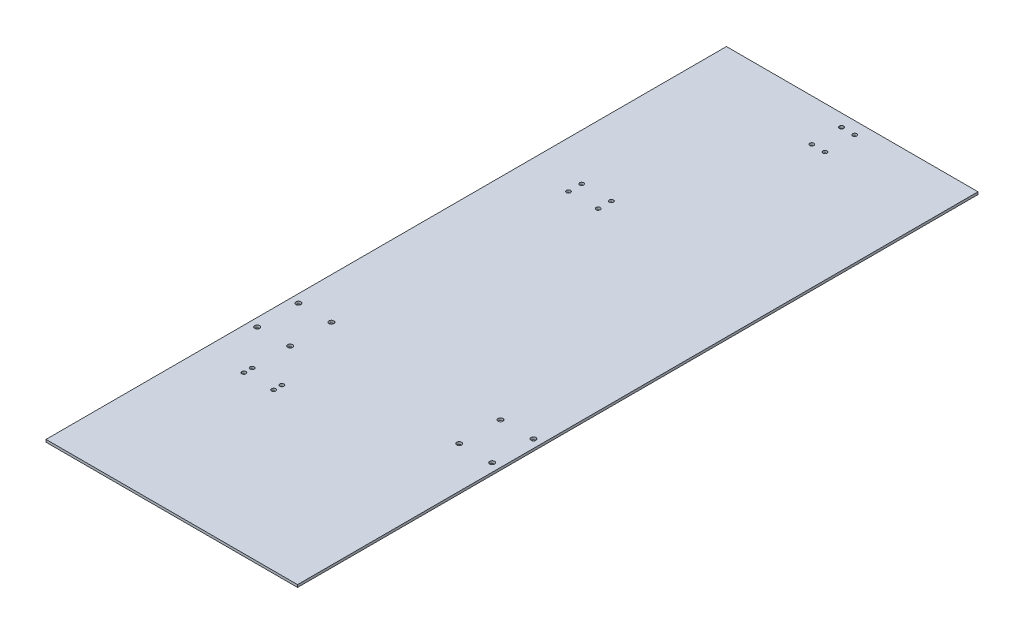
SolidWorks part; units mm, degrees
ref_plane "Front Plane" through (0, 0, 0) normal (0, 0, 1) x (1, 0, 0)
ref_plane "Top Plane" through (0, 0, 0) normal (0, 1, 0) x (1, 0, 0)
ref_plane "Right Plane" through (0, 0, 0) normal (1, 0, 0) x (0, 0, -1)
sketch "Sketch1" plane through (0, 0, 0) normal (0, 1, 0) x (1, 0, 0)
  line L0 (-118, 150) -> (-171, 150)
  line L1 (-118, 150) -> (118, 150)
  line L3 (-118, -150) -> (118, -150)
  line L4 (118, 150) -> (118, -150)
  line L5 (-118, 150) -> (118, -150) construction
  line L6 (-118, -150) -> (118, 150) construction
  line L7 (-171, 150) -> (-171, -150)
  line L8 (-171, -150) -> (-118, -150)
  point P0 (0, 0)
  dimension "D1" = 236
  dimension "D2" = 300
  dimension "D3" = 53
extrude "Boss-Extrude1" add sketch "Sketch1" along normal blind 3
sketch "Sketch2" plane through (0, 3, 0) normal (0, 1, 0) x (1, 0, 0)
  line L3 (-171, 150) -> (-171, -150) construction
  line L5 (118, 150) -> (-171, 150) construction
  circle A21 centre (-129, 50) radius 2.5
  circle A22 centre (-129, 40) radius 2.5
  circle A23 centre (-93, 40) radius 2.5
  circle A24 centre (-93, 50) radius 2.5
  point P0 (0, 0)
  dimension "D3" = 36
  dimension "D10" = 100
  dimension "D8" = 42
  dimension "D9" = 10
  dimension "D2" = 36
extrude "Cut-Extrude3" cut sketch "Sketch2" against normal blind 20
sketch "Sketch3" plane through (0, 0, -150) normal (0, 0, -1) x (-1, 0, 0)
  line L4 (-118, 0) -> (171, 0)
  line L5 (171, 0) -> (171, 3)
  line L6 (171, 3) -> (-118, 3)
  line L7 (-118, 3) -> (-118, 0)
  line L8 (-118, 0) -> (171, 0)
  line L9 (171, 0) -> (171, 3)
  line L10 (171, 3) -> (-118, 3)
  line L11 (-118, 3) -> (-118, 0)
  dimension "D1" = 0
extrude "Boss-Extrude2" add sketch "Sketch3" along normal blind 600
sketch "Sketch4" plane through (0, 3, 0) normal (0, 1, 0) x (1, 0, 0)
  line L0 (-16.5, 356.1307) -> (-16.5, 683.0402) construction
  line L1 (118, -150) -> (118, 750) construction
  line L7 (-171, 750) -> (118, 750) construction
  circle A0 centre (-8.5, 660) radius 2.5
  circle A1 centre (-8.5, 624) radius 2.5
  circle A14 centre (-24.5, 624) radius 2.5
  circle A15 centre (-24.5, 660) radius 2.5
  dimension "D2" = 90
  dimension "D4" = 36
  dimension "D1" = 134.5
  dimension "D3" = 8
extrude "Cut-Extrude4" cut sketch "Sketch4" against normal blind 10
sketch "Sketch5" plane through (0, 3, 0) normal (0, 1, 0) x (1, 0, 0)
  line L0 (-171, 675) -> (118, 675)
  line L1 (-171, 750) -> (-171, -150) construction
  line L2 (118, -150) -> (118, 750) construction
  line L3 (-171, 750) -> (118, 750) construction
  line L4 (118, 675) -> (118, 750)
  line L5 (118, 750) -> (-171, 750)
  line L6 (-171, 750) -> (-171, 675)
  dimension "D1" = 75
extrude "Cut-Extrude5" cut sketch "Sketch5" against normal blind 10
sketch "Sketch6" plane through (0, 3, 0) normal (0, 1, 0) x (1, 0, 0)
  line L0 (118, -150) -> (118, 675) construction
  line L1 (-171, 675) -> (118, 675) construction
  line L2 (-16.5, 435) -> (-171, 435)
  line L3 (-171, 675) -> (-171, -150) construction
  circle A1 centre (-122.5, 427) radius 2.5
  circle A2 centre (-86.5, 427) radius 2.5
  circle A3 centre (-86.5, 443) radius 2.5
  circle A4 centre (-122.5, 443) radius 2.5
  dimension "D1" = 134.5
  dimension "D3" = 8
  dimension "D5" = 36
  dimension "D2" = 240
  dimension "D4" = 48.5
extrude "Cut-Extrude6" cut sketch "Sketch6" against normal blind 5 contours A3 | A2 | A1 | A4
sketch "Sketch7" plane through (0, 3, 0) normal (0, 1, 0) x (1, 0, 0)
  line L1 (-171, -150) -> (-179, -150)
  line L2 (-171, -150) -> (-171, 675)
  line L3 (-171, 675) -> (-179, 675)
  line L4 (-179, -150) -> (-179, 675)
  line L5 (118, -150) -> (126, -150)
  line L6 (118, -150) -> (118, 675)
  line L7 (118, 675) -> (126, 675)
  line L8 (126, -150) -> (126, 675)
  dimension "D1" = 8
  dimension "D2" = 8
extrude "Boss-Extrude3" add sketch "Sketch7" against normal through all
sketch "Sketch8" plane through (0, 3, 0) normal (0, 1, 0) x (1, 0, 0)
  line L0 (-179, 675) -> (-179, -150) construction
  line L1 (-149, 126.0949) -> (-149, 76.0949) construction
  line L2 (-179, -150) -> (126, -150) construction
  line L3 (-26.5, 76.0949) -> (-26.5, 220.3636) construction
  circle A0 centre (-169, 96) radius 3
  circle A1 centre (-169, 146) radius 3
  circle A2 centre (-129, 96) radius 3
  circle A3 centre (-129, 146) radius 3
  circle A4 centre (116, 96) radius 3
  circle A5 centre (76, 96) radius 3
  circle A6 centre (76, 146) radius 3
  circle A7 centre (116, 146) radius 3
  dimension "D1" = 10
  dimension "D2" = 50
  dimension "D3" = 30
  dimension "D4" = 246
  dimension "D5" = 152.5
extrude "Cut-Extrude7" cut sketch "Sketch8" against normal through all
